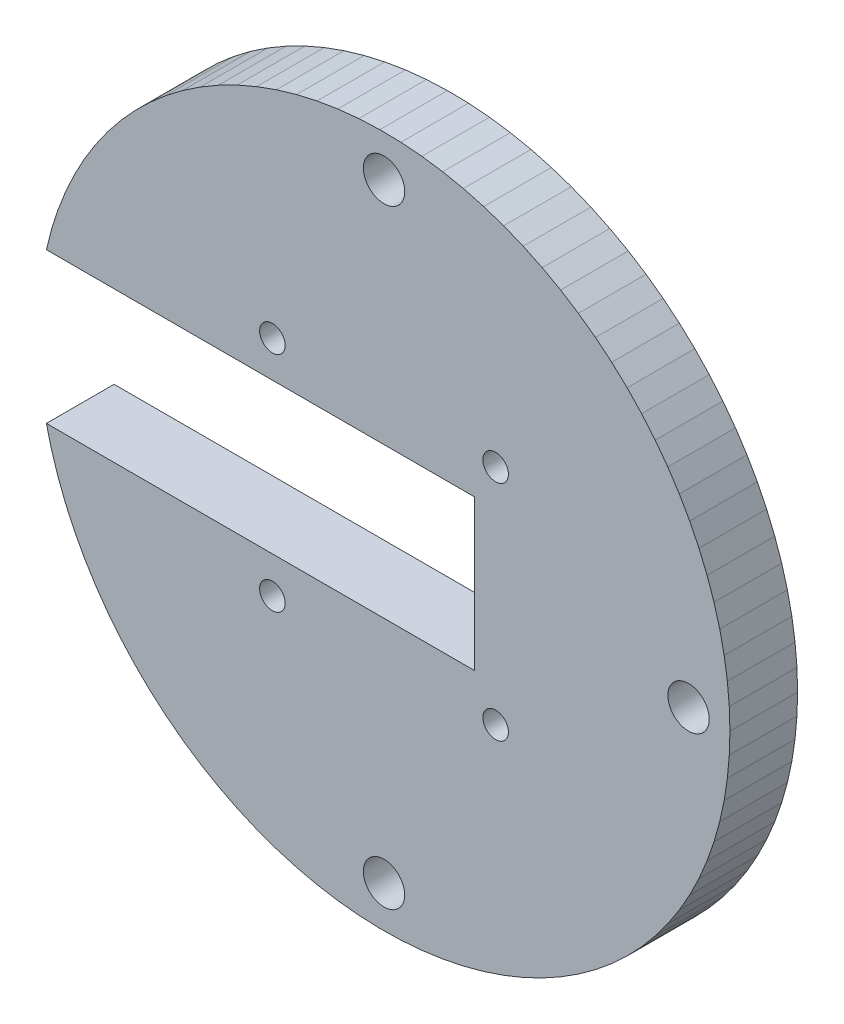
SolidWorks part; units mm, degrees
ref_plane "前视基准面" through (0, 0, 0) normal (0, 0, 1) x (1, 0, 0)
ref_plane "上视基准面" through (0, 0, 0) normal (0, 1, 0) x (1, 0, 0)
ref_plane "右视基准面" through (0, 0, 0) normal (1, 0, 0) x (0, 0, -1)
other "Configuration Table"
sketch "草图1" plane through (0, 0, 0) normal (0, 0, 1) x (1, 0, 0)
  line L0 (-44.8999, -10) -> (-44.2082, -12.7135)
  line L1 (-44.2082, -12.7135) -> (-43.3527, -15.3799)
  line L2 (-43.3527, -15.3799) -> (-42.3366, -17.9892)
  line L3 (-42.3366, -17.9892) -> (-41.1636, -20.532)
  line L4 (-41.1636, -20.532) -> (-39.838, -22.9986)
  line L5 (-39.838, -22.9986) -> (-38.3648, -25.38)
  line L6 (-38.3648, -25.38) -> (-36.7494, -27.6673)
  line L7 (-36.7494, -27.6673) -> (-34.9978, -29.8521)
  line L8 (-34.9978, -29.8521) -> (-33.1166, -31.9263)
  line L9 (-33.1166, -31.9263) -> (-31.1126, -33.8822)
  line L10 (-31.1126, -33.8822) -> (-28.9933, -35.7125)
  line L11 (-28.9933, -35.7125) -> (-26.7666, -37.4105)
  line L12 (-26.7666, -37.4105) -> (-24.4407, -38.9699)
  line L13 (-24.4407, -38.9699) -> (-22.0242, -40.3848)
  line L14 (-22.0242, -40.3848) -> (-19.5261, -41.6501)
  line L15 (-19.5261, -41.6501) -> (-16.9557, -42.761)
  line L16 (-16.9557, -42.761) -> (-14.3224, -43.7135)
  line L17 (-14.3224, -43.7135) -> (-11.636, -44.504)
  line L18 (-11.636, -44.504) -> (-8.9066, -45.1295)
  line L19 (-8.9066, -45.1295) -> (-6.1441, -45.5878)
  line L20 (-6.1441, -45.5878) -> (-3.3588, -45.8772)
  line L21 (-3.3588, -45.8772) -> (-0.5611, -45.9966)
  line L22 (-0.5611, -45.9966) -> (2.2387, -45.9455)
  line L23 (2.2387, -45.9455) -> (5.0302, -45.7241)
  line L24 (5.0302, -45.7241) -> (7.803, -45.3334)
  line L25 (7.803, -45.3334) -> (10.5469, -44.7746)
  line L26 (10.5469, -44.7746) -> (13.2518, -44.0499)
  line L27 (13.2518, -44.0499) -> (15.9075, -43.1619)
  line L28 (15.9075, -43.1619) -> (18.5043, -42.114)
  line L29 (18.5043, -42.114) -> (21.0325, -40.9101)
  line L30 (21.0325, -40.9101) -> (23.4828, -39.5545)
  line L31 (23.4828, -39.5545) -> (25.8461, -38.0523)
  line L32 (25.8461, -38.0523) -> (28.1135, -36.4092)
  line L33 (28.1135, -36.4092) -> (30.2768, -34.6311)
  line L34 (30.2768, -34.6311) -> (32.3279, -32.7247)
  line L35 (32.3279, -32.7247) -> (34.2592, -30.697)
  line L36 (34.2592, -30.697) -> (36.0636, -28.5556)
  line L37 (36.0636, -28.5556) -> (37.7342, -26.3083)
  line L38 (37.7342, -26.3083) -> (39.2651, -23.9635)
  line L39 (39.2651, -23.9635) -> (40.6505, -21.53)
  line L40 (40.6505, -21.53) -> (41.8852, -19.0166)
  line L41 (41.8852, -19.0166) -> (42.9647, -16.4328)
  line L42 (42.9647, -16.4328) -> (43.8849, -13.7881)
  line L43 (43.8849, -13.7881) -> (44.6426, -11.0923)
  line L44 (44.6426, -11.0923) -> (45.2348, -8.3554)
  line L45 (45.2348, -8.3554) -> (45.6594, -5.5875)
  line L46 (45.6594, -5.5875) -> (45.9148, -2.799)
  line L47 (45.9148, -2.799) -> (46, 0)
  line L48 (46, 0) -> (45.9148, 2.799)
  line L49 (45.9148, 2.799) -> (45.6594, 5.5875)
  line L50 (45.6594, 5.5875) -> (45.2348, 8.3554)
  line L51 (45.2348, 8.3554) -> (44.6426, 11.0923)
  line L52 (44.6426, 11.0923) -> (43.8849, 13.7881)
  line L53 (43.8849, 13.7881) -> (42.9647, 16.4328)
  line L54 (42.9647, 16.4328) -> (41.8852, 19.0166)
  line L55 (41.8852, 19.0166) -> (40.6505, 21.53)
  line L56 (40.6505, 21.53) -> (39.2651, 23.9635)
  line L57 (39.2651, 23.9635) -> (37.7342, 26.3083)
  line L58 (37.7342, 26.3083) -> (36.0636, 28.5556)
  line L59 (36.0636, 28.5556) -> (34.2592, 30.697)
  line L60 (34.2592, 30.697) -> (32.3279, 32.7247)
  line L61 (32.3279, 32.7247) -> (30.2768, 34.6311)
  line L62 (30.2768, 34.6311) -> (28.1135, 36.4092)
  line L63 (28.1135, 36.4092) -> (25.8461, 38.0523)
  line L64 (25.8461, 38.0523) -> (23.4828, 39.5545)
  line L65 (23.4828, 39.5545) -> (21.0325, 40.9101)
  line L66 (21.0325, 40.9101) -> (18.5043, 42.114)
  line L67 (18.5043, 42.114) -> (15.9075, 43.1619)
  line L68 (15.9075, 43.1619) -> (13.2518, 44.0499)
  line L69 (13.2518, 44.0499) -> (10.5469, 44.7746)
  line L70 (10.5469, 44.7746) -> (7.803, 45.3334)
  line L71 (7.803, 45.3334) -> (5.0302, 45.7241)
  line L72 (5.0302, 45.7241) -> (2.2387, 45.9455)
  line L73 (2.2387, 45.9455) -> (-0.5611, 45.9966)
  line L74 (-0.5611, 45.9966) -> (-3.3588, 45.8772)
  line L75 (-3.3588, 45.8772) -> (-6.1441, 45.5878)
  line L76 (-6.1441, 45.5878) -> (-8.9066, 45.1295)
  line L77 (-8.9066, 45.1295) -> (-11.636, 44.504)
  line L78 (-11.636, 44.504) -> (-14.3224, 43.7135)
  line L79 (-14.3224, 43.7135) -> (-16.9557, 42.761)
  line L80 (-16.9557, 42.761) -> (-19.5261, 41.6501)
  line L81 (-19.5261, 41.6501) -> (-22.0242, 40.3848)
  line L82 (-22.0242, 40.3848) -> (-24.4407, 38.9699)
  line L83 (-24.4407, 38.9699) -> (-26.7666, 37.4105)
  line L84 (-26.7666, 37.4105) -> (-28.9933, 35.7125)
  line L85 (-28.9933, 35.7125) -> (-31.1126, 33.8822)
  line L86 (-31.1126, 33.8822) -> (-33.1166, 31.9263)
  line L87 (-33.1166, 31.9263) -> (-34.9978, 29.8521)
  line L88 (-34.9978, 29.8521) -> (-36.7494, 27.6673)
  line L89 (-36.7494, 27.6673) -> (-38.3648, 25.38)
  line L90 (-38.3648, 25.38) -> (-39.838, 22.9986)
  line L91 (-39.838, 22.9986) -> (-41.1636, 20.532)
  line L92 (-41.1636, 20.532) -> (-42.3366, 17.9892)
  line L93 (-42.3366, 17.9892) -> (-43.3527, 15.3799)
  line L94 (-43.3527, 15.3799) -> (-44.2082, 12.7135)
  line L95 (-44.2082, 12.7135) -> (-44.8999, 10)
  line L96 (-44.8999, 10) -> (12, 10)
  line L97 (12, 10) -> (12, -10)
  line L98 (12, -10) -> (-44.8999, -10)
  circle A0 centre (-14.845, -14.845) radius 3.75
  circle A1 centre (-14.845, 14.845) radius 3.75
  circle A2 centre (14.845, -14.845) radius 3.75
  circle A3 centre (14.845, 14.845) radius 3.75
  circle A4 centre (0, -40.5) radius 2.75
  circle A5 centre (0, 40.5) radius 2.75
  circle A6 centre (40.5, 0) radius 2.75
extrude "底层与螺钉头避空" add sketch "草图1" along normal blind 4 from offset 0
sketch "草图2" plane through (0, 0, 0) normal (0, 0, 1) x (1, 0, 0)
  line L0 (-44.8999, -10) -> (-44.2082, -12.7135)
  line L1 (-44.2082, -12.7135) -> (-43.3527, -15.3799)
  line L2 (-43.3527, -15.3799) -> (-42.3366, -17.9892)
  line L3 (-42.3366, -17.9892) -> (-41.1636, -20.532)
  line L4 (-41.1636, -20.532) -> (-39.838, -22.9986)
  line L5 (-39.838, -22.9986) -> (-38.3648, -25.38)
  line L6 (-38.3648, -25.38) -> (-36.7494, -27.6673)
  line L7 (-36.7494, -27.6673) -> (-34.9978, -29.8521)
  line L8 (-34.9978, -29.8521) -> (-33.1166, -31.9263)
  line L9 (-33.1166, -31.9263) -> (-31.1126, -33.8822)
  line L10 (-31.1126, -33.8822) -> (-28.9933, -35.7125)
  line L11 (-28.9933, -35.7125) -> (-26.7666, -37.4105)
  line L12 (-26.7666, -37.4105) -> (-24.4407, -38.9699)
  line L13 (-24.4407, -38.9699) -> (-22.0242, -40.3848)
  line L14 (-22.0242, -40.3848) -> (-19.5261, -41.6501)
  line L15 (-19.5261, -41.6501) -> (-16.9557, -42.761)
  line L16 (-16.9557, -42.761) -> (-14.3224, -43.7135)
  line L17 (-14.3224, -43.7135) -> (-11.636, -44.504)
  line L18 (-11.636, -44.504) -> (-8.9066, -45.1295)
  line L19 (-8.9066, -45.1295) -> (-6.1441, -45.5878)
  line L20 (-6.1441, -45.5878) -> (-3.3588, -45.8772)
  line L21 (-3.3588, -45.8772) -> (-0.5611, -45.9966)
  line L22 (-0.5611, -45.9966) -> (2.2387, -45.9455)
  line L23 (2.2387, -45.9455) -> (5.0302, -45.7241)
  line L24 (5.0302, -45.7241) -> (7.803, -45.3334)
  line L25 (7.803, -45.3334) -> (10.5469, -44.7746)
  line L26 (10.5469, -44.7746) -> (13.2518, -44.0499)
  line L27 (13.2518, -44.0499) -> (15.9075, -43.1619)
  line L28 (15.9075, -43.1619) -> (18.5043, -42.114)
  line L29 (18.5043, -42.114) -> (21.0325, -40.9101)
  line L30 (21.0325, -40.9101) -> (23.4828, -39.5545)
  line L31 (23.4828, -39.5545) -> (25.8461, -38.0523)
  line L32 (25.8461, -38.0523) -> (28.1135, -36.4092)
  line L33 (28.1135, -36.4092) -> (30.2768, -34.6311)
  line L34 (30.2768, -34.6311) -> (32.3279, -32.7247)
  line L35 (32.3279, -32.7247) -> (34.2592, -30.697)
  line L36 (34.2592, -30.697) -> (36.0636, -28.5556)
  line L37 (36.0636, -28.5556) -> (37.7342, -26.3083)
  line L38 (37.7342, -26.3083) -> (39.2651, -23.9635)
  line L39 (39.2651, -23.9635) -> (40.6505, -21.53)
  line L40 (40.6505, -21.53) -> (41.8852, -19.0166)
  line L41 (41.8852, -19.0166) -> (42.9647, -16.4328)
  line L42 (42.9647, -16.4328) -> (43.8849, -13.7881)
  line L43 (43.8849, -13.7881) -> (44.6426, -11.0923)
  line L44 (44.6426, -11.0923) -> (45.2348, -8.3554)
  line L45 (45.2348, -8.3554) -> (45.6594, -5.5875)
  line L46 (45.6594, -5.5875) -> (45.9148, -2.799)
  line L47 (45.9148, -2.799) -> (46, 0)
  line L48 (46, 0) -> (45.9148, 2.799)
  line L49 (45.9148, 2.799) -> (45.6594, 5.5875)
  line L50 (45.6594, 5.5875) -> (45.2348, 8.3554)
  line L51 (45.2348, 8.3554) -> (44.6426, 11.0923)
  line L52 (44.6426, 11.0923) -> (43.8849, 13.7881)
  line L53 (43.8849, 13.7881) -> (42.9647, 16.4328)
  line L54 (42.9647, 16.4328) -> (41.8852, 19.0166)
  line L55 (41.8852, 19.0166) -> (40.6505, 21.53)
  line L56 (40.6505, 21.53) -> (39.2651, 23.9635)
  line L57 (39.2651, 23.9635) -> (37.7342, 26.3083)
  line L58 (37.7342, 26.3083) -> (36.0636, 28.5556)
  line L59 (36.0636, 28.5556) -> (34.2592, 30.697)
  line L60 (34.2592, 30.697) -> (32.3279, 32.7247)
  line L61 (32.3279, 32.7247) -> (30.2768, 34.6311)
  line L62 (30.2768, 34.6311) -> (28.1135, 36.4092)
  line L63 (28.1135, 36.4092) -> (25.8461, 38.0523)
  line L64 (25.8461, 38.0523) -> (23.4828, 39.5545)
  line L65 (23.4828, 39.5545) -> (21.0325, 40.9101)
  line L66 (21.0325, 40.9101) -> (18.5043, 42.114)
  line L67 (18.5043, 42.114) -> (15.9075, 43.1619)
  line L68 (15.9075, 43.1619) -> (13.2518, 44.0499)
  line L69 (13.2518, 44.0499) -> (10.5469, 44.7746)
  line L70 (10.5469, 44.7746) -> (7.803, 45.3334)
  line L71 (7.803, 45.3334) -> (5.0302, 45.7241)
  line L72 (5.0302, 45.7241) -> (2.2387, 45.9455)
  line L73 (2.2387, 45.9455) -> (-0.5611, 45.9966)
  line L74 (-0.5611, 45.9966) -> (-3.3588, 45.8772)
  line L75 (-3.3588, 45.8772) -> (-6.1441, 45.5878)
  line L76 (-6.1441, 45.5878) -> (-8.9066, 45.1295)
  line L77 (-8.9066, 45.1295) -> (-11.636, 44.504)
  line L78 (-11.636, 44.504) -> (-14.3224, 43.7135)
  line L79 (-14.3224, 43.7135) -> (-16.9557, 42.761)
  line L80 (-16.9557, 42.761) -> (-19.5261, 41.6501)
  line L81 (-19.5261, 41.6501) -> (-22.0242, 40.3848)
  line L82 (-22.0242, 40.3848) -> (-24.4407, 38.9699)
  line L83 (-24.4407, 38.9699) -> (-26.7666, 37.4105)
  line L84 (-26.7666, 37.4105) -> (-28.9933, 35.7125)
  line L85 (-28.9933, 35.7125) -> (-31.1126, 33.8822)
  line L86 (-31.1126, 33.8822) -> (-33.1166, 31.9263)
  line L87 (-33.1166, 31.9263) -> (-34.9978, 29.8521)
  line L88 (-34.9978, 29.8521) -> (-36.7494, 27.6673)
  line L89 (-36.7494, 27.6673) -> (-38.3648, 25.38)
  line L90 (-38.3648, 25.38) -> (-39.838, 22.9986)
  line L91 (-39.838, 22.9986) -> (-41.1636, 20.532)
  line L92 (-41.1636, 20.532) -> (-42.3366, 17.9892)
  line L93 (-42.3366, 17.9892) -> (-43.3527, 15.3799)
  line L94 (-43.3527, 15.3799) -> (-44.2082, 12.7135)
  line L95 (-44.2082, 12.7135) -> (-44.8999, 10)
  line L96 (-44.8999, 10) -> (12, 10)
  line L97 (12, 10) -> (12, -10)
  line L98 (12, -10) -> (-44.8999, -10)
  circle A0 centre (-14.845, -14.845) radius 1.7
  circle A1 centre (-14.845, 14.845) radius 1.7
  circle A2 centre (14.845, -14.845) radius 1.7
  circle A3 centre (14.845, 14.845) radius 1.7
  circle A4 centre (0, -40.5) radius 2.75
  circle A5 centre (0, 40.5) radius 2.75
  circle A6 centre (40.5, 0) radius 2.75
extrude "上层与通孔" add sketch "草图2" along normal blind 5 from offset 4
